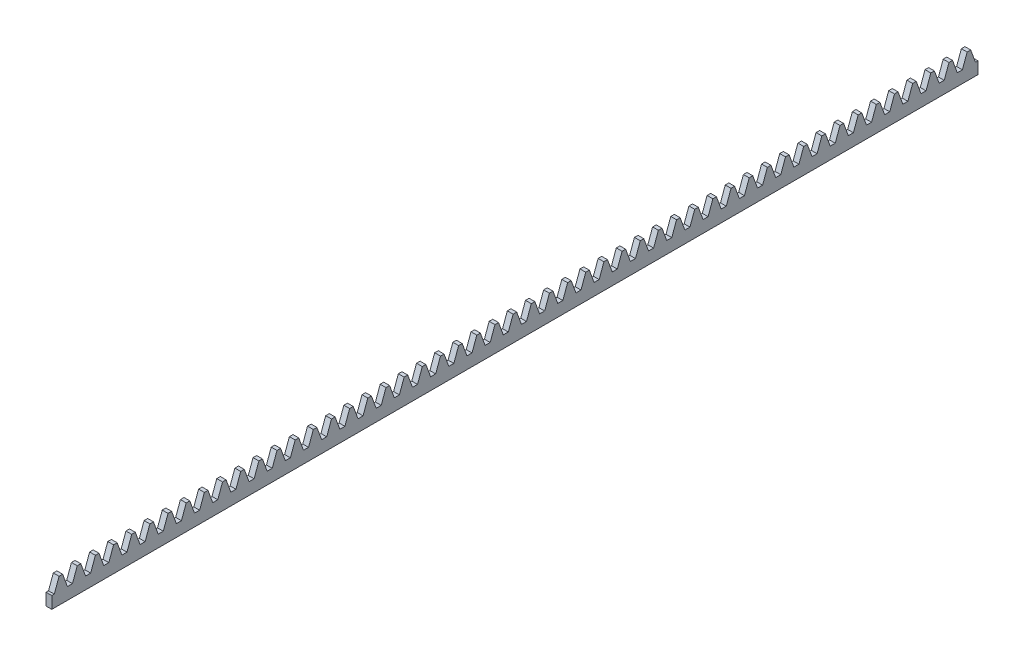
SolidWorks part; units mm, degrees
ref_plane "Plano frontal" through (0, 0, 0) normal (0, 0, 1) x (1, 0, 0)
ref_plane "Plano superior" through (0, 0, 0) normal (0, 1, 0) x (1, 0, 0)
ref_plane "Plano direito" through (0, 0, 0) normal (1, 0, 0) x (0, 0, -1)
sketch "Esboço1" plane through (0, 0, 0) normal (0, 0, 1) x (1, 0, 0)
  line L1 (0, 0) -> (3, 0)
  line L2 (0, 0) -> (0, 13)
  line L3 (0, 13) -> (3, 13)
  line L4 (3, 0) -> (3, 13)
  dimension "D1" = 13
  dimension "D2" = 3
extrude "Ressalto-extrusão1" add sketch "Esboço1" along normal blind 480.664
sketch "Esboço2" plane through (0, 0, 0) normal (-1, 0, 0) x (0, 0, 1)
  line L0 (1.3123, 6.2246) -> (-1.3123, 6.2246)
  line L1 (3.7784, 13) -> (1.3123, 6.2246)
  line L2 (3.7784, 13) -> (-3.7784, 13)
  line L3 (-3.7784, 13) -> (-1.3123, 6.2246)
  line L4 (10.7371, 6.2246) -> (8.1125, 6.2246)
  line L5 (480.664, 13) -> (0, 13) construction
  line L6 (0, 0) -> (0, 20.9677) construction
  line L7 (13.2031, 13) -> (10.7371, 6.2246)
  line L8 (13.2031, 13) -> (5.6464, 13)
  line L9 (5.6464, 13) -> (8.1125, 6.2246)
  line L10 (20.1619, 6.2246) -> (17.5372, 6.2246)
  line L11 (22.6279, 13) -> (20.1619, 6.2246)
  line L12 (22.6279, 13) -> (15.0712, 13)
  line L13 (15.0712, 13) -> (17.5372, 6.2246)
  line L14 (29.5866, 6.2246) -> (26.962, 6.2246)
  line L15 (32.0527, 13) -> (29.5866, 6.2246)
  line L16 (32.0527, 13) -> (24.496, 13)
  line L17 (24.496, 13) -> (26.962, 6.2246)
  line L18 (39.0114, 6.2246) -> (36.3868, 6.2246)
  line L19 (41.4775, 13) -> (39.0114, 6.2246)
  line L20 (41.4775, 13) -> (33.9208, 13)
  line L21 (33.9208, 13) -> (36.3868, 6.2246)
  line L22 (48.4362, 6.2246) -> (45.8116, 6.2246)
  line L23 (50.9022, 13) -> (48.4362, 6.2246)
  line L24 (50.9022, 13) -> (43.3455, 13)
  line L25 (43.3455, 13) -> (45.8116, 6.2246)
  line L26 (57.861, 6.2246) -> (55.2364, 6.2246)
  line L27 (60.327, 13) -> (57.861, 6.2246)
  line L28 (60.327, 13) -> (52.7703, 13)
  line L29 (52.7703, 13) -> (55.2364, 6.2246)
  line L30 (67.2858, 6.2246) -> (64.6611, 6.2246)
  line L31 (69.7518, 13) -> (67.2858, 6.2246)
  line L32 (69.7518, 13) -> (62.1951, 13)
  line L33 (62.1951, 13) -> (64.6611, 6.2246)
  line L34 (76.7105, 6.2246) -> (74.0859, 6.2246)
  line L35 (79.1766, 13) -> (76.7105, 6.2246)
  line L36 (79.1766, 13) -> (71.6199, 13)
  line L37 (71.6199, 13) -> (74.0859, 6.2246)
  line L38 (86.1353, 6.2246) -> (83.5107, 6.2246)
  line L39 (88.6014, 13) -> (86.1353, 6.2246)
  line L40 (88.6014, 13) -> (81.0447, 13)
  line L41 (81.0447, 13) -> (83.5107, 6.2246)
  line L42 (95.5601, 6.2246) -> (92.9355, 6.2246)
  line L43 (98.0261, 13) -> (95.5601, 6.2246)
  line L44 (98.0261, 13) -> (90.4694, 13)
  line L45 (90.4694, 13) -> (92.9355, 6.2246)
  line L46 (104.9849, 6.2246) -> (102.3603, 6.2246)
  line L47 (107.4509, 13) -> (104.9849, 6.2246)
  line L48 (107.4509, 13) -> (99.8942, 13)
  line L49 (99.8942, 13) -> (102.3603, 6.2246)
  line L50 (114.4096, 6.2246) -> (111.785, 6.2246)
  line L51 (116.8757, 13) -> (114.4096, 6.2246)
  line L52 (116.8757, 13) -> (109.319, 13)
  line L53 (109.319, 13) -> (111.785, 6.2246)
  line L54 (123.8344, 6.2246) -> (121.2098, 6.2246)
  line L55 (126.3005, 13) -> (123.8344, 6.2246)
  line L56 (126.3005, 13) -> (118.7438, 13)
  line L57 (118.7438, 13) -> (121.2098, 6.2246)
  line L58 (133.2592, 6.2246) -> (130.6346, 6.2246)
  line L59 (135.7252, 13) -> (133.2592, 6.2246)
  line L60 (135.7252, 13) -> (128.1685, 13)
  line L61 (128.1685, 13) -> (130.6346, 6.2246)
  line L62 (142.684, 6.2246) -> (140.0594, 6.2246)
  line L63 (145.15, 13) -> (142.684, 6.2246)
  line L64 (145.15, 13) -> (137.5933, 13)
  line L65 (137.5933, 13) -> (140.0594, 6.2246)
  line L66 (152.1088, 6.2246) -> (149.4841, 6.2246)
  line L67 (154.5748, 13) -> (152.1088, 6.2246)
  line L68 (154.5748, 13) -> (147.0181, 13)
  line L69 (147.0181, 13) -> (149.4841, 6.2246)
  line L70 (161.5335, 6.2246) -> (158.9089, 6.2246)
  line L71 (163.9996, 13) -> (161.5335, 6.2246)
  line L72 (163.9996, 13) -> (156.4429, 13)
  line L73 (156.4429, 13) -> (158.9089, 6.2246)
  line L74 (170.9583, 6.2246) -> (168.3337, 6.2246)
  line L75 (173.4244, 13) -> (170.9583, 6.2246)
  line L76 (173.4244, 13) -> (165.8677, 13)
  line L77 (165.8677, 13) -> (168.3337, 6.2246)
  line L78 (180.3831, 6.2246) -> (177.7585, 6.2246)
  line L79 (182.8491, 13) -> (180.3831, 6.2246)
  line L80 (182.8491, 13) -> (175.2924, 13)
  line L81 (175.2924, 13) -> (177.7585, 6.2246)
  line L82 (189.8079, 6.2246) -> (187.1833, 6.2246)
  line L83 (192.2739, 13) -> (189.8079, 6.2246)
  line L84 (192.2739, 13) -> (184.7172, 13)
  line L85 (184.7172, 13) -> (187.1833, 6.2246)
  line L86 (199.2326, 6.2246) -> (196.608, 6.2246)
  line L87 (201.6987, 13) -> (199.2326, 6.2246)
  line L88 (201.6987, 13) -> (194.142, 13)
  line L89 (194.142, 13) -> (196.608, 6.2246)
  line L90 (208.6574, 6.2246) -> (206.0328, 6.2246)
  line L91 (211.1235, 13) -> (208.6574, 6.2246)
  line L92 (211.1235, 13) -> (203.5668, 13)
  line L93 (203.5668, 13) -> (206.0328, 6.2246)
  line L94 (218.0822, 6.2246) -> (215.4576, 6.2246)
  line L95 (220.5482, 13) -> (218.0822, 6.2246)
  line L96 (220.5482, 13) -> (212.9915, 13)
  line L97 (212.9915, 13) -> (215.4576, 6.2246)
  line L98 (227.507, 6.2246) -> (224.8824, 6.2246)
  line L99 (229.973, 13) -> (227.507, 6.2246)
  line L100 (229.973, 13) -> (222.4163, 13)
  line L101 (222.4163, 13) -> (224.8824, 6.2246)
  line L102 (236.9318, 6.2246) -> (234.3071, 6.2246)
  line L103 (239.3978, 13) -> (236.9318, 6.2246)
  line L104 (239.3978, 13) -> (231.8411, 13)
  line L105 (231.8411, 13) -> (234.3071, 6.2246)
  line L106 (246.3565, 6.2246) -> (243.7319, 6.2246)
  line L107 (248.8226, 13) -> (246.3565, 6.2246)
  line L108 (248.8226, 13) -> (241.2659, 13)
  line L109 (241.2659, 13) -> (243.7319, 6.2246)
  line L110 (255.7813, 6.2246) -> (253.1567, 6.2246)
  line L111 (258.2474, 13) -> (255.7813, 6.2246)
  line L112 (258.2474, 13) -> (250.6907, 13)
  line L113 (250.6907, 13) -> (253.1567, 6.2246)
  line L114 (265.2061, 6.2246) -> (262.5815, 6.2246)
  line L115 (267.6721, 13) -> (265.2061, 6.2246)
  line L116 (267.6721, 13) -> (260.1154, 13)
  line L117 (260.1154, 13) -> (262.5815, 6.2246)
  line L118 (274.6309, 6.2246) -> (272.0063, 6.2246)
  line L119 (277.0969, 13) -> (274.6309, 6.2246)
  line L120 (277.0969, 13) -> (269.5402, 13)
  line L121 (269.5402, 13) -> (272.0063, 6.2246)
  line L122 (284.0556, 6.2246) -> (281.431, 6.2246)
  line L123 (286.5217, 13) -> (284.0556, 6.2246)
  line L124 (286.5217, 13) -> (278.965, 13)
  line L125 (278.965, 13) -> (281.431, 6.2246)
  line L126 (293.4804, 6.2246) -> (290.8558, 6.2246)
  line L127 (295.9465, 13) -> (293.4804, 6.2246)
  line L128 (295.9465, 13) -> (288.3898, 13)
  line L129 (288.3898, 13) -> (290.8558, 6.2246)
  line L130 (302.9052, 6.2246) -> (300.2806, 6.2246)
  line L131 (305.3712, 13) -> (302.9052, 6.2246)
  line L132 (305.3712, 13) -> (297.8145, 13)
  line L133 (297.8145, 13) -> (300.2806, 6.2246)
  line L134 (312.33, 6.2246) -> (309.7054, 6.2246)
  line L135 (314.796, 13) -> (312.33, 6.2246)
  line L136 (314.796, 13) -> (307.2393, 13)
  line L137 (307.2393, 13) -> (309.7054, 6.2246)
  line L138 (321.7548, 6.2246) -> (319.1301, 6.2246)
  line L139 (324.2208, 13) -> (321.7548, 6.2246)
  line L140 (324.2208, 13) -> (316.6641, 13)
  line L141 (316.6641, 13) -> (319.1301, 6.2246)
  line L142 (331.1795, 6.2246) -> (328.5549, 6.2246)
  line L143 (333.6456, 13) -> (331.1795, 6.2246)
  line L144 (333.6456, 13) -> (326.0889, 13)
  line L145 (326.0889, 13) -> (328.5549, 6.2246)
  line L146 (340.6043, 6.2246) -> (337.9797, 6.2246)
  line L147 (343.0704, 13) -> (340.6043, 6.2246)
  line L148 (343.0704, 13) -> (335.5137, 13)
  line L149 (335.5137, 13) -> (337.9797, 6.2246)
  line L150 (350.0291, 6.2246) -> (347.4045, 6.2246)
  line L151 (352.4951, 13) -> (350.0291, 6.2246)
  line L152 (352.4951, 13) -> (344.9384, 13)
  line L153 (344.9384, 13) -> (347.4045, 6.2246)
  line L154 (359.4539, 6.2246) -> (356.8293, 6.2246)
  line L155 (361.9199, 13) -> (359.4539, 6.2246)
  line L156 (361.9199, 13) -> (354.3632, 13)
  line L157 (354.3632, 13) -> (356.8293, 6.2246)
  line L158 (368.8786, 6.2246) -> (366.254, 6.2246)
  line L159 (371.3447, 13) -> (368.8786, 6.2246)
  line L160 (371.3447, 13) -> (363.788, 13)
  line L161 (363.788, 13) -> (366.254, 6.2246)
  line L162 (378.3034, 6.2246) -> (375.6788, 6.2246)
  line L163 (380.7695, 13) -> (378.3034, 6.2246)
  line L164 (380.7695, 13) -> (373.2128, 13)
  line L165 (373.2128, 13) -> (375.6788, 6.2246)
  line L166 (387.7282, 6.2246) -> (385.1036, 6.2246)
  line L167 (390.1942, 13) -> (387.7282, 6.2246)
  line L168 (390.1942, 13) -> (382.6375, 13)
  line L169 (382.6375, 13) -> (385.1036, 6.2246)
  line L170 (397.153, 6.2246) -> (394.5284, 6.2246)
  line L171 (399.619, 13) -> (397.153, 6.2246)
  line L172 (399.619, 13) -> (392.0623, 13)
  line L173 (392.0623, 13) -> (394.5284, 6.2246)
  line L174 (406.5778, 6.2246) -> (403.9531, 6.2246)
  line L175 (409.0438, 13) -> (406.5778, 6.2246)
  line L176 (409.0438, 13) -> (401.4871, 13)
  line L177 (401.4871, 13) -> (403.9531, 6.2246)
  line L178 (416.0025, 6.2246) -> (413.3779, 6.2246)
  line L179 (418.4686, 13) -> (416.0025, 6.2246)
  line L180 (418.4686, 13) -> (410.9119, 13)
  line L181 (410.9119, 13) -> (413.3779, 6.2246)
  line L182 (425.4273, 6.2246) -> (422.8027, 6.2246)
  line L183 (427.8934, 13) -> (425.4273, 6.2246)
  line L184 (427.8934, 13) -> (420.3367, 13)
  line L185 (420.3367, 13) -> (422.8027, 6.2246)
  line L186 (434.8521, 6.2246) -> (432.2275, 6.2246)
  line L187 (437.3181, 13) -> (434.8521, 6.2246)
  line L188 (437.3181, 13) -> (429.7614, 13)
  line L189 (429.7614, 13) -> (432.2275, 6.2246)
  line L190 (444.2769, 6.2246) -> (441.6523, 6.2246)
  line L191 (446.7429, 13) -> (444.2769, 6.2246)
  line L192 (446.7429, 13) -> (439.1862, 13)
  line L193 (439.1862, 13) -> (441.6523, 6.2246)
  line L194 (453.7016, 6.2246) -> (451.077, 6.2246)
  line L195 (456.1677, 13) -> (453.7016, 6.2246)
  line L196 (456.1677, 13) -> (448.611, 13)
  line L197 (448.611, 13) -> (451.077, 6.2246)
  line L198 (463.1264, 6.2246) -> (460.5018, 6.2246)
  line L199 (465.5925, 13) -> (463.1264, 6.2246)
  line L200 (465.5925, 13) -> (458.0358, 13)
  line L201 (458.0358, 13) -> (460.5018, 6.2246)
  line L202 (472.5512, 6.2246) -> (469.9266, 6.2246)
  line L203 (475.0172, 13) -> (472.5512, 6.2246)
  line L204 (475.0172, 13) -> (467.4605, 13)
  line L205 (467.4605, 13) -> (469.9266, 6.2246)
  line L206 (481.976, 6.2246) -> (479.3514, 6.2246)
  line L207 (484.442, 13) -> (481.976, 6.2246)
  line L208 (484.442, 13) -> (476.8853, 13)
  line L209 (476.8853, 13) -> (479.3514, 6.2246)
  dimension "D1" = 2.6246
  dimension "D2" = 7.5567
  dimension "D3" = 6.7754
  dimension "D4" = 52
  dimension "D5" = 1.8681
extrude "Corte-extrusão1" cut sketch "Esboço2" against normal through all
